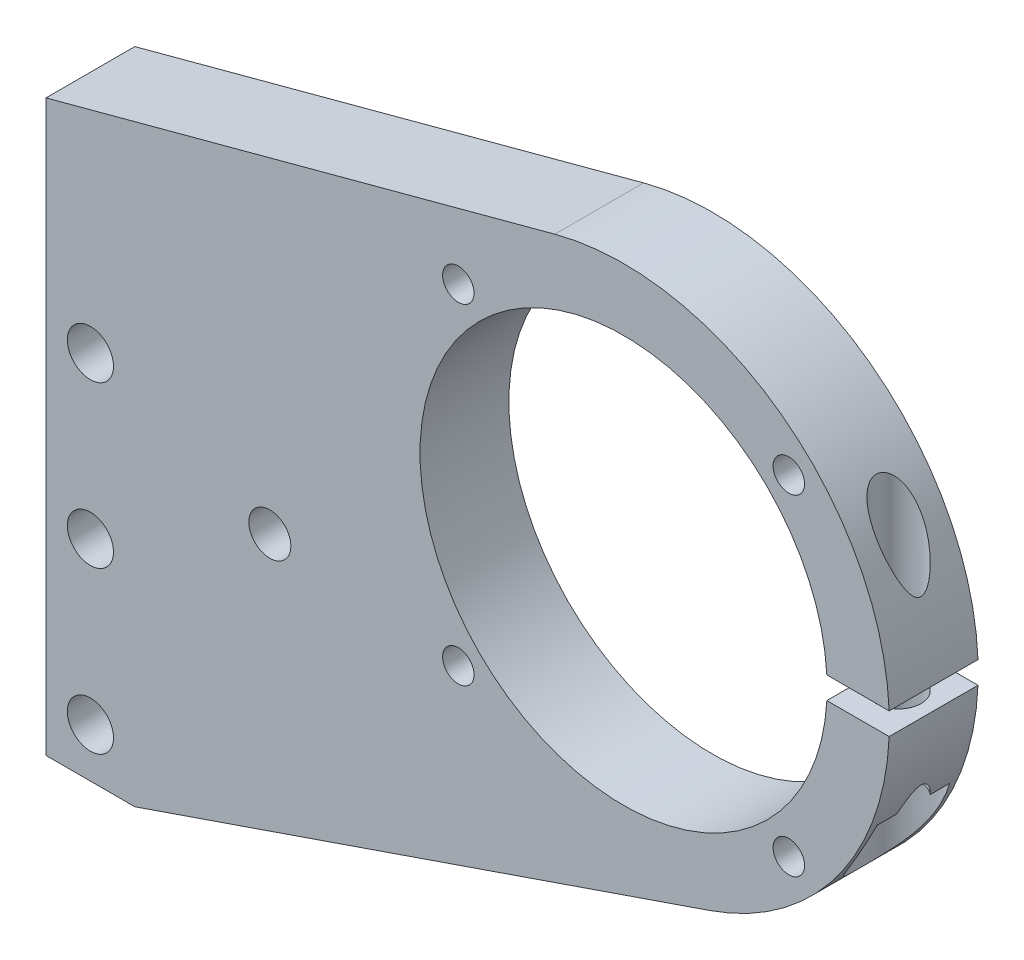
SolidWorks part; units mm, degrees
material "6061 Alloy"
ref_plane "Front" through (0, 0, 0) normal (0, 0, 1) x (1, 0, 0)
ref_plane "Top" through (0, 0, 0) normal (0, 1, 0) x (1, 0, 0)
ref_plane "Right" through (0, 0, 0) normal (1, 0, 0) x (0, 0, -1)
ref_plane "Plane1" through (0, 0, 0) normal (0, 0, -1) x (-1, 0, 0)
sketch "Sketch1" plane through (0, 0, 0) normal (0, 0, -1) x (-1, 0, 0)
  line L0 (129.2465, 74.5705) -> (211.4695, 46.305)
  line L1 (211.4695, 46.305) -> (224.1695, 46.305)
  line L2 (224.1695, 46.305) -> (224.1695, 127.7225)
  line L3 (224.1695, 127.7225) -> (151.4352, 147.2116)
  arc A0 (151.4352, 147.2116) -> (129.2465, 74.5705) centre (141.6001, 110.5064) ccw
extrude "Boss-Extrude1" add sketch "Sketch1" against normal blind 12.7
sketch "Sketch2" plane through (0, 0, 12.7) normal (0, 0, 1) x (1, 0, 0)
  line L0 (-103.6333, 112.0939) -> (-113.0692, 112.0939)
  line L1 (-113.0692, 108.9189) -> (-103.6333, 108.9189)
  arc A0 (-103.6333, 108.9189) -> (-103.6333, 112.0939) centre (-141.6001, 110.5064) ccw
  arc A1 (-113.0692, 112.0939) -> (-113.0692, 108.9189) centre (-141.6001, 110.5064) cw
extrude "Cut-Extrude1" cut sketch "Sketch2" against normal through all
ref_plane "Plane2" through (0, 110.5064, 0) normal (0, -1, 0) x (1, 0, 0)
sketch "Sketch3" plane through (0, 110.5064, 0) normal (0, -1, 0) x (1, 0, 0)
  line L0 (-112.5001, 12.7) -> (-141.6001, 12.7)
  line L1 (-141.6001, 12.7) -> (-141.6001, 0)
  line L2 (-141.6001, 0) -> (-112.5001, 0)
  line L3 (-112.5001, 0) -> (-112.5001, 12.7)
  line L4 (-141.6001, 12.7) -> (-141.6001, 0) construction
  dimension "D1" = 29.1
revolve "Cut-Revolve1" cut sketch "Sketch3" angle 360 about L4
hole_wizard "#12 Clearance Hole1" positions "Sketch5" profile "Sketch4" hole size "#12" standard "ANSI Inch"
sketch "Sketch5" plane through (0, 0, 12.7) normal (0, 0, 1) x (1, 0, 0)
  point P0 (-192.1695, 89.7225)
sketch "Sketch4" plane through (-192.1695, 89.7225, 12.7) normal (1, 0, 0) x (0, -1, 0)
  line L0 (0, 0) -> (0, 12.7)
  line L1 (0, 12.7) -> (3, 12.7)
  line L2 (3, 12.7) -> (3, 0)
  line L5 (3, 0) -> (0, 0)
  line L11 (0, -6.35) -> (0, 107.95) construction
  dimension "Thru Hole Dia." = 6
  dimension "Thru Hole Depth" = 12.7
hole_wizard "#8 Clearance Hole1" positions "Sketch7" profile "Sketch6" hole size "#8" standard "ANSI Inch"
sketch "Sketch7" plane through (0, 0, 12.7) normal (0, 0, 1) x (1, 0, 0)
  point P0 (-117.9781, 86.8844)
  point P1 (-165.2221, 86.8844)
  point P2 (-165.2221, 134.1284)
  point P3 (-117.9781, 134.1284)
sketch "Sketch6" plane through (-117.9781, 86.8844, 12.7) normal (1, 0, 0) x (0, -1, 0)
  line L0 (0, 0) -> (0, 12.7)
  line L1 (0, 12.7) -> (2.25, 12.7)
  line L2 (2.25, 12.7) -> (2.25, 0)
  line L5 (2.25, 0) -> (0, 0)
  line L11 (0, -6.35) -> (0, 107.95) construction
  dimension "Thru Hole Dia." = 4.5
  dimension "Thru Hole Depth" = 12.7
hole_wizard "1/4 Clearance Hole1" positions "Sketch9" profile "Sketch8" hole size "1/4" standard "ANSI Inch"
sketch "Sketch9" plane through (0, 0, 0) normal (0, 0, -1) x (-1, 0, 0)
  point P0 (217.8195, 53.305)
  point P1 (217.8195, 76.305)
  point P2 (217.8195, 99.305)
sketch "Sketch8" plane through (-217.8195, 53.305, 0) normal (1, 0, 0) x (0, 1, 0)
  line L0 (0, 0) -> (0, 12.7)
  line L1 (0, 12.7) -> (3.3, 12.7)
  line L2 (3.3, 12.7) -> (3.3, 0)
  line L5 (3.3, 0) -> (0, 0)
  line L11 (0, -6.35) -> (0, 107.95) construction
  dimension "Thru Hole Dia." = 6.6
  dimension "Thru Hole Depth" = 12.7
hole_wizard "#10 Clearance Hole1" positions "Sketch11" profile "Sketch10" hole size "#10" standard "ANSI Inch"
sketch "Sketch11" plane through (0, 112.0939, 0) normal (0, -1, 0) x (-1, 0, 0)
  point P0 (108.6333, -6.35)
sketch "Sketch10" plane through (-108.6333, 112.0939, 6.35) normal (1, 0, 0) x (0, 0, -1)
  line L0 (0, 0) -> (0, 36.4125)
  line L1 (0, 36.4125) -> (2.5, 36.4125)
  line L2 (2.5, 36.4125) -> (2.5, 0)
  line L5 (2.5, 0) -> (0, 0)
  line L11 (0, -6.35) -> (0, 107.95) construction
  dimension "Thru Hole Dia." = 5
  dimension "Thru Hole Depth" = 36.4125
ref_plane "Plane3" through (0, 84.1425, 0) normal (0, -1, 0) x (-1, 0, 0)
hole_wizard "Hole1" positions "Sketch13" profile "Sketch12" legacy
sketch "Sketch13" plane through (0, 84.1425, 0) normal (0, -1, 0) x (-1, 0, 0)
  point P0 (108.6333, -6.35)
sketch "Sketch12" plane through (-108.6333, 84.1425, 6.35) normal (1, 0, 0) x (0, 0, -1)
  line L0 (0, 0) -> (0, 64.3639)
  line L1 (0, 64.3639) -> (3.2, 64.3639)
  line L2 (3.2, 64.3639) -> (3.2, 11.7764)
  line L3 (3.2, 11.7764) -> (5.6, 11.7764)
  line L4 (5.6, 11.7764) -> (5.6, 0)
  line L5 (5.6, 0) -> (0, 0)
  line L6 (0, 110) -> (0, -10) construction
  dimension "Diameter" = 6.4
  dimension "Depth" = 64.3639
  dimension "C-Bore Diameter" = 11.2
  dimension "C-Bore Depth" = 11.7764
chamfer "Chamfer1" distance 3 angle 45 3 edges at (-221.1195, 53.305, 0) (-221.1195, 76.305, 0) (-221.1195, 99.305, 0)
